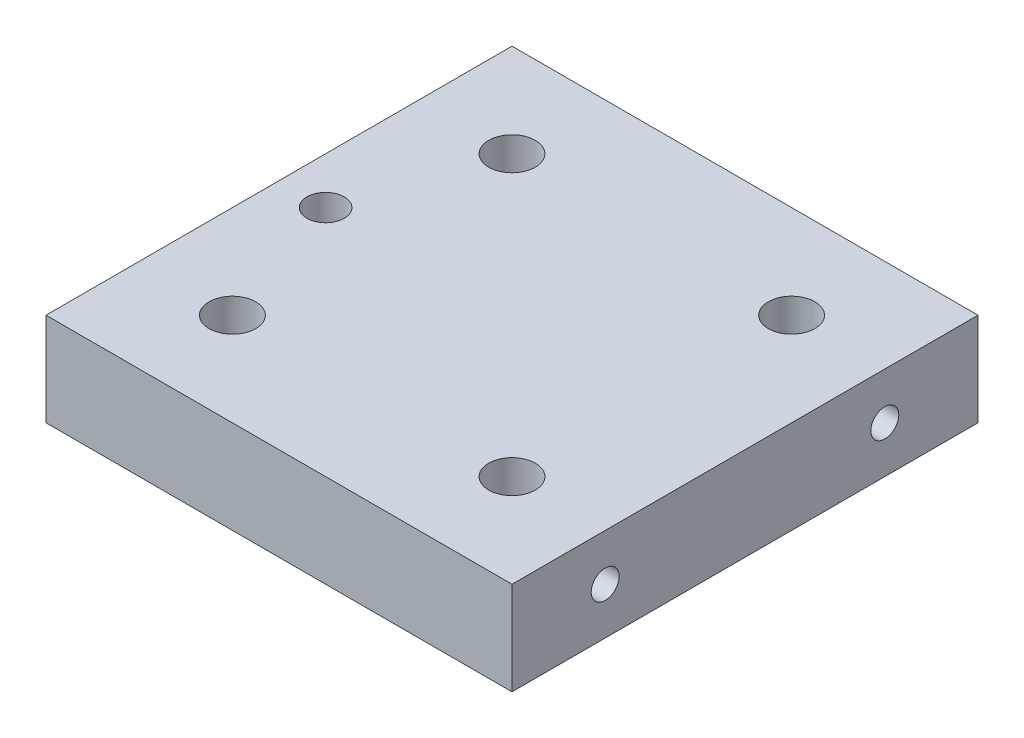
SolidWorks part; units mm, degrees
material "Сосна"
ref_plane "Спереди" through (0, 0, 0) normal (0, 0, 1) x (1, 0, 0)
ref_plane "Сверху" through (0, 0, 0) normal (0, 1, 0) x (1, 0, 0)
ref_plane "Справа" through (0, 0, 0) normal (1, 0, 0) x (0, 0, -1)
sketch "Эскиз1" plane through (0, 0, 0) normal (0, 1, 0) x (1, 0, 0)
  line L1 (0, 0) -> (100, 0)
  line L2 (0, 0) -> (0, 100)
  line L3 (0, 100) -> (100, 100)
  line L4 (100, 0) -> (100, 100)
  dimension "D1" = 100
  dimension "D2" = 100
extrude "Бобышка-Вытянуть1" add sketch "Эскиз1" along normal blind 20
sketch "Эскиз2" plane through (0, 0, 0) normal (0, -1, 0) x (1, 0, 0)
  line L0 (0, 0) -> (100, 0) construction
  line L1 (100, -100) -> (0, -100) construction
  line L2 (0, -100) -> (0, 0) construction
  line L3 (100, 0) -> (100, -100) construction
  line L4 (0, -50) -> (21.726, -50) construction
  circle A0 centre (20, -20) radius 5
  circle A1 centre (10, -50) radius 4
  circle A2 centre (20, -80) radius 5
  circle A3 centre (80, -20) radius 5
  circle A5 centre (80, -80) radius 5
  dimension "D1" = 20
  dimension "D7" = 10
  dimension "D9" = 10
  dimension "D10" = 20
  dimension "D16" = 10
  dimension "D18" = 10
  dimension "D3" = 8
  dimension "D2" = 20
  dimension "D4" = 20
  dimension "D5" = 10
  dimension "D6" = 20
  dimension "D11" = 20
  dimension "D13" = 20
  dimension "D15" = 20
extrude "Вырез-Вытянуть1" cut sketch "Эскиз2" against normal blind 20
sketch "Эскиз3" plane through (0, 0, 0) normal (-1, 0, 0) x (0, 0, 1)
  line L0 (-100, 10) -> (0, 10) construction
  line L1 (-100, 20) -> (-100, 0) construction
  line L2 (0, 20) -> (0, 0) construction
  circle A0 centre (-80, 10) radius 3
  circle A2 centre (-20, 10) radius 3
  dimension "D1" = 20
  dimension "D3" = 6
  dimension "D5" = 6
  dimension "D2" = 20
extrude "Вырез-Вытянуть2" cut sketch "Эскиз3" against normal blind 20
sketch "Эскиз4" plane through (100, 0, 0) normal (1, 0, 0) x (0, 0, -1)
  line L0 (0, 10) -> (100, 10) construction
  line L1 (0, 20) -> (0, 0) construction
  line L2 (100, 20) -> (100, 0) construction
  circle A0 centre (20, 10) radius 3
  circle A2 centre (80, 10) radius 3
  dimension "D1" = 20
  dimension "D3" = 6
  dimension "D5" = 6
  dimension "D2" = 20
extrude "Вырез-Вытянуть3" cut sketch "Эскиз4" against normal blind 20
